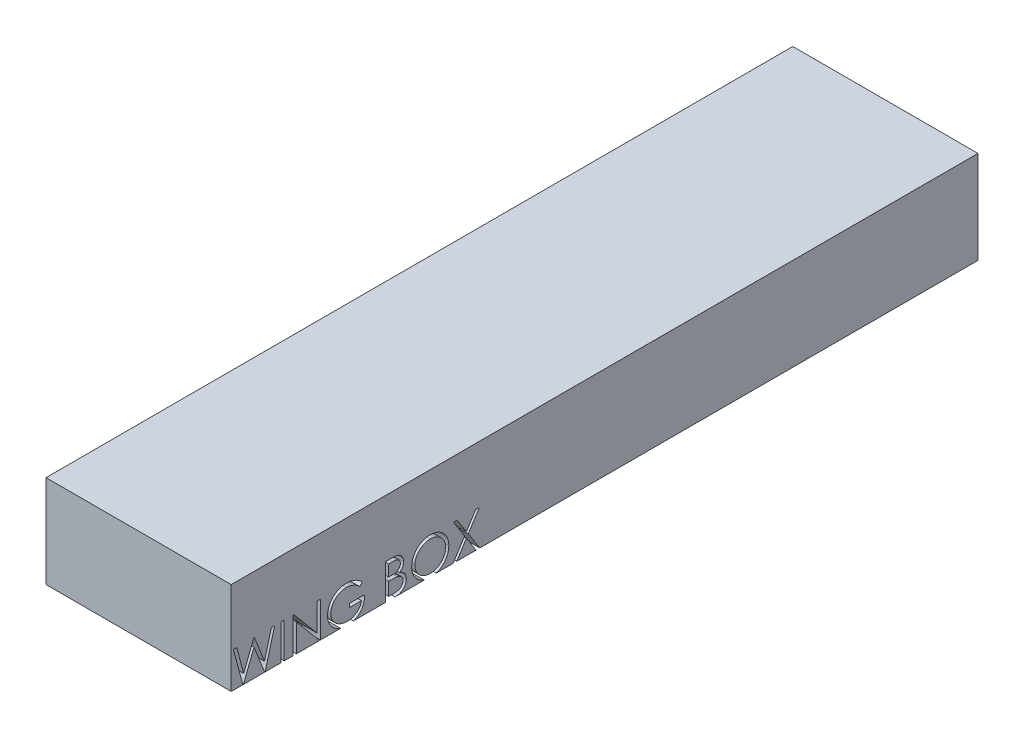
SolidWorks part; units mm, degrees
ref_plane "Front Plane" through (0, 0, 0) normal (0, 0, 1) x (1, 0, 0)
ref_plane "Top Plane" through (0, 0, 0) normal (0, 1, 0) x (1, 0, 0)
ref_plane "Right Plane" through (0, 0, 0) normal (1, 0, 0) x (0, 0, -1)
sketch "Sketch1" plane through (0, 0, 0) normal (1, 0, 0) x (0, 0, -1)
  line L1 (-403.2, 50) -> (0, 50)
  line L2 (-403.2, 50) -> (-403.2, 0)
  line L3 (-403.2, 0) -> (0, 0)
  line L4 (0, 50) -> (0, 0)
  dimension "D1" = 50
  dimension "D2" = 403.2
extrude "Boss-Extrude1" add sketch "Sketch1" along normal mid plane 100
sketch "Sketch2" plane through (50, 0, 0) normal (1, 0, 0) x (0, 0, -1)
  line L0 (-403.2, 50) -> (-403.2, 0) construction
  line L1 (-403.2, 0) -> (0, 0) construction
  text T0 "WING BOX\r\n" font "Century Gothic" height in points 72
extrude "Cut-Extrude1" cut sketch "Sketch2" against normal blind 10
